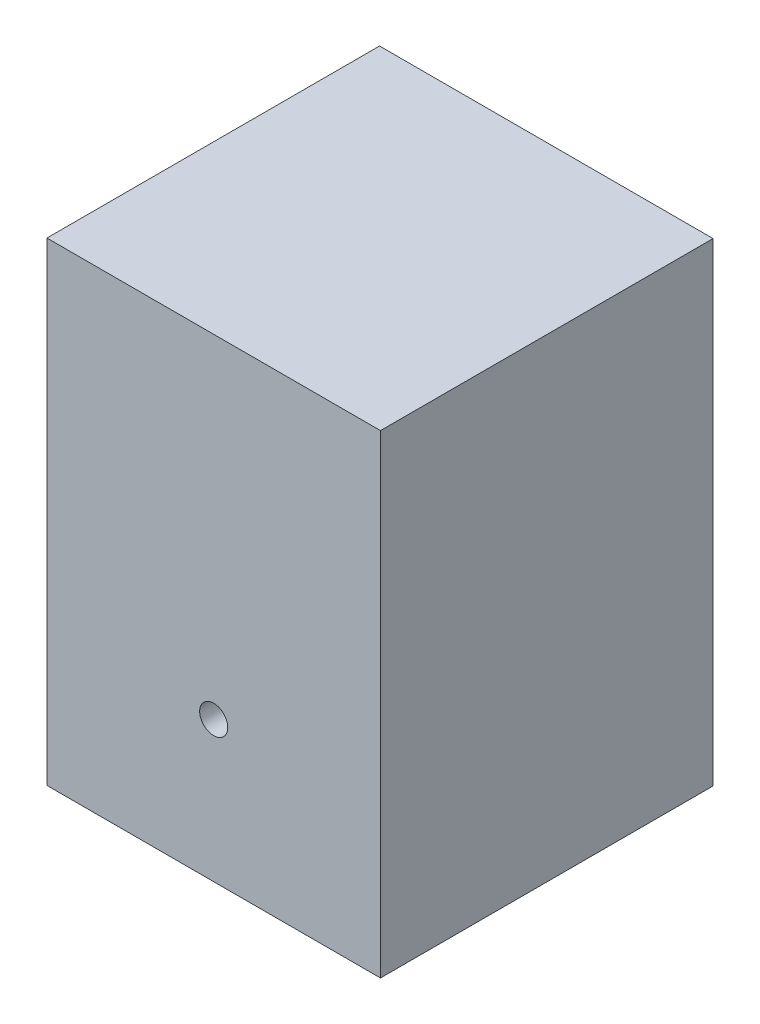
SolidWorks part; units mm, degrees
ref_plane "前视基准面" through (0, 0, 0) normal (0, 0, 1) x (1, 0, 0)
ref_plane "上视基准面" through (0, 0, 0) normal (0, 1, 0) x (1, 0, 0)
ref_plane "右视基准面" through (0, 0, 0) normal (1, 0, 0) x (0, 0, -1)
sketch "草图1" plane through (0, 0, 0) normal (0, 0, 1) x (1, 0, 0)
  line L1 (0, 0) -> (35.6, 0)
  line L2 (0, 0) -> (0, 50.6)
  line L3 (0, 50.6) -> (35.6, 50.6)
  line L4 (35.6, 0) -> (35.6, 50.6)
  dimension "D1" = 35.6
  dimension "D2" = 50.6
extrude "凸台-拉伸1" add sketch "草图1" along normal blind 35.5
sketch "草图2" plane through (0, 0, 35.5) normal (0, 0, 1) x (1, 0, 0)
  line L0 (17.8, 0) -> (17.8, 50.6) construction
  line L1 (0, 0) -> (35.6, 0) construction
  line L2 (35.6, 50.6) -> (0, 50.6) construction
  circle A0 centre (17.8, 15) radius 1.5
  dimension "D1" = 3
  dimension "D2" = 15
extrude "切除-拉伸1" cut sketch "草图2" against normal blind 7
